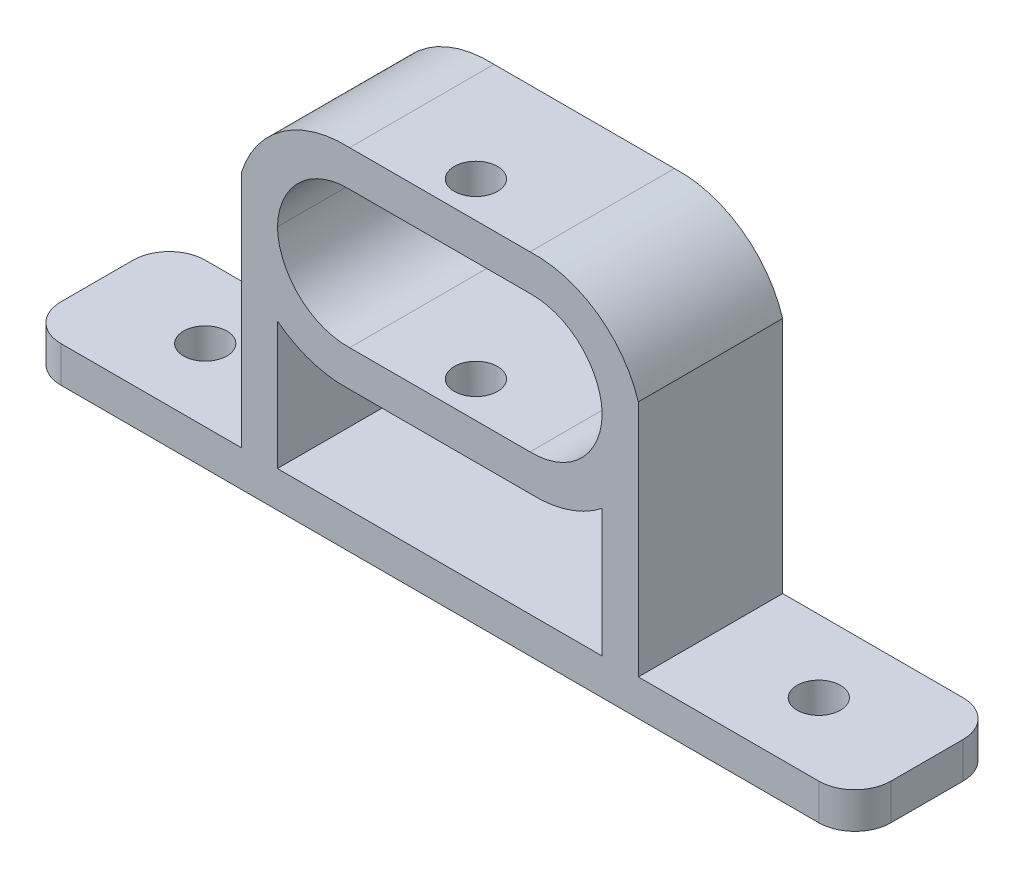
SolidWorks part; units mm, degrees
ref_plane "Alzado" through (0, 0, 0) normal (0, 0, 1) x (1, 0, 0)
ref_plane "Planta" through (0, 0, 0) normal (0, 1, 0) x (1, 0, 0)
ref_plane "Vista lateral" through (0, 0, 0) normal (1, 0, 0) x (0, 0, -1)
sketch "Croquis1" plane through (0, 0, 0) normal (0, 0, 1) x (1, 0, 0)
  line L0 (0, 3.25) -> (25, 3.25)
  line L1 (0, -6.25) -> (0, 3.25) construction
  line L2 (0, -20.75) -> (25, -20.75)
  line L5 (0, 8.25) -> (25, 8.25)
  line L6 (0, -15.75) -> (25, -15.75)
  line L7 (40, -6.25) -> (40, -2.25)
  line L8 (40, -6.25) -> (40, -10.25)
  line L9 (0, -6.25) -> (0, -15.75) construction
  line L10 (0, -6.25) -> (25, -6.25) construction
  line L11 (40, -6.25) -> (35, -6.25) construction
  line L12 (25, -6.25) -> (35, -6.25) construction
  line L13 (12.5, 8.25) -> (12.5, 19.8706) construction
  line L14 (0, -6.25) -> (-10, -6.25) construction
  line L15 (-15, -6.25) -> (-10, -6.25) construction
  line L16 (-15, -6.25) -> (-15, -10.25)
  line L17 (-15, -6.25) -> (-15, -2.25)
  arc A0 (25, 8.25) -> (40, -2.25) centre (25.686, -6.7343) cw
  arc A1 (25, 3.25) -> (35, -6.25) centre (25.25, -6.5) cw
  arc A2 (25, -15.75) -> (35, -6.25) centre (25.25, -6) ccw
  arc A3 (25, -20.75) -> (40, -10.25) centre (25.686, -5.7657) ccw
  arc A4 (0, -20.75) -> (-15, -10.25) centre (-0.686, -5.7657) cw
  arc A5 (0, -15.75) -> (-10, -6.25) centre (-0.25, -6) cw
  arc A6 (0, 3.25) -> (-10, -6.25) centre (-0.25, -6.5) ccw
  arc A7 (0, 8.25) -> (-15, -2.25) centre (-0.686, -6.7343) ccw
  dimension "D1" = 5
  dimension "D2" = 9.5
  dimension "D3" = 5
  dimension "D4" = 4
  dimension "D7" = 10
  dimension "D9" = 25
extrude "Saliente-Extruir1" add sketch "Croquis1" along normal blind 20
sketch "Croquis3" plane through (0, 0, 20) normal (0, 0, 1) x (1, 0, 0)
  line L0 (40, -10.25) -> (40, -35.25)
  line L1 (40, -40.25) -> (-15, -40.25)
  line L2 (12.5, -40.25) -> (12.5, -35.25) construction
  line L3 (-10, -35.25) -> (35, -35.25)
  line L4 (35, -35.25) -> (40, -35.25) construction
  line L5 (35, -35.25) -> (35, -17.5236)
  line L6 (-10, -35.25) -> (-10, -17.5236)
  line L7 (-15, -10.25) -> (-15, -35.25)
  line L8 (40, -40.25) -> (70, -40.25)
  line L9 (70, -40.25) -> (70, -35.25)
  line L10 (70, -35.25) -> (40, -35.25)
  line L11 (-45, -35.25) -> (-15, -35.25)
  line L12 (-45, -40.25) -> (-45, -35.25)
  line L13 (-15, -40.25) -> (-45, -40.25)
  arc A0 (25, -20.75) -> (40, -10.25) centre (25.686, -5.7657) ccw construction
  arc A1 (35, -17.5236) -> (40, -10.25) centre (25.686, -5.7657) ccw
  arc A2 (-10, -17.5236) -> (-15, -10.25) centre (-0.686, -5.7657) cw
  dimension "D1" = 5
  dimension "D2" = 30
  dimension "D3" = 5
  dimension "D4" = 30
sketch "Croquis4" plane through (0, 8.25, 0) normal (0, 1, 0) x (1, 0, 0)
  line L0 (12.5, -15) -> (12.5, 0) construction
  line L2 (25, 0) -> (0, 0) construction
  circle A1 centre (12.5, -15) radius 3
  dimension "D1" = 6
  dimension "D2" = 15
extrude "Saliente-Extruir2" add sketch "Croquis3" against normal through all
extrude "Cortar-Extruir2" cut sketch "Croquis4" against normal up to surface (29 mm away) up to face at (12.5, -20.75, 10)
fillet "Redondeo1" radius 5 4 edges at (-45, -37.75, 20) (-45, -37.75, 0) (70, -37.75, 20) (70, -37.75, 0)
sketch "Croquis5" plane through (0, -35.25, 0) normal (0, 1, 0) x (1, 0, 0)
  line L0 (-45, -10) -> (-30, -10) construction
  line L1 (-45, -5) -> (-45, -15) construction
  line L2 (12.5, -20) -> (12.5, -15.7429) construction
  line L3 (35, -20) -> (-10, -20) construction
  circle A0 centre (-30, -10) radius 3
  circle A1 centre (55, -10) radius 3
  dimension "D1" = 15
extrude "Cortar-Extruir3" cut sketch "Croquis5" against normal up to next
